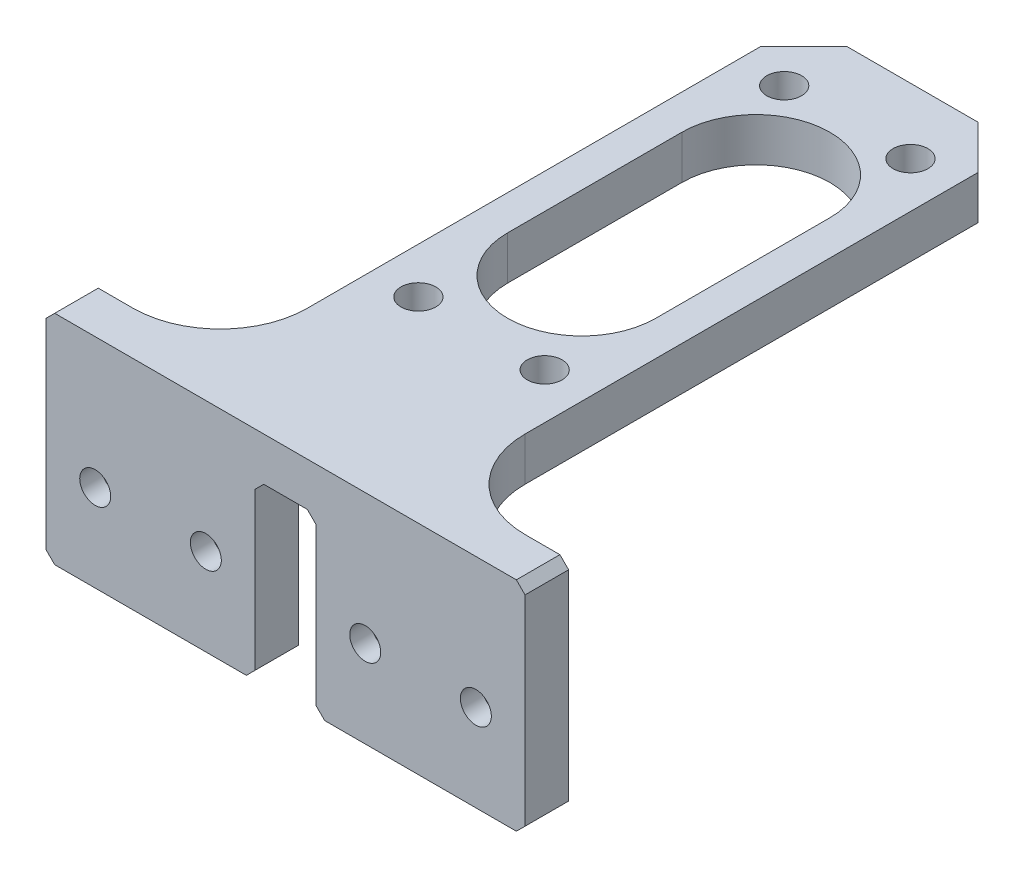
SolidWorks part; units mm, degrees
ref_plane "Front Plane" through (0, 0, 0) normal (0, 0, 1) x (1, 0, 0)
ref_plane "Top Plane" through (0, 0, 0) normal (0, 1, 0) x (1, 0, 0)
ref_plane "Right Plane" through (0, 0, 0) normal (1, 0, 0) x (0, 0, -1)
sketch "Sketch1" plane through (0, 0, 0) normal (0, 1, 0) x (1, 0, 0)
  line L0 (0, 0) -> (0, 23.7757) construction
  line L1 (-12.5, -36) -> (12.5, -36)
  line L2 (-12.5, -36) -> (-12.5, 36)
  line L3 (-12.5, 36) -> (12.5, 36)
  line L4 (12.5, -36) -> (12.5, 36)
  line L5 (-12.5, -36) -> (12.5, 36) construction
  line L6 (-12.5, 36) -> (12.5, -36) construction
  line L7 (-12.5, -36) -> (-27.5, -36)
  line L8 (-12.5, -36) -> (-12.5, -31)
  line L9 (-12.5, -31) -> (-27.5, -31)
  line L10 (-27.5, -36) -> (-27.5, -31)
  line L11 (12.5, -36) -> (27.5, -36)
  line L12 (12.5, -36) -> (12.5, -31)
  line L13 (12.5, -31) -> (27.5, -31)
  line L14 (27.5, -36) -> (27.5, -31)
  point P0 (0, 0)
  dimension "D1" = 25
  dimension "D2" = 72
  dimension "D3" = 55
  dimension "D4" = 5
extrude "Boss-Extrude1" add sketch "Sketch1" along normal blind 5 contours L1 L4 L3 L2 | L10 L7 L2 L9 | L11 L14 L13 L4
sketch "Sketch2" plane through (0, 5, 0) normal (0, 1, 0) x (1, 0, 0)
  line L0 (0, 0) -> (0, 22.8648) construction
  line L1 (-12.5, 36) -> (12.5, 36) construction
  line L2 (-27.5, -36) -> (27.5, -36) construction
  circle A0 centre (-7.25, 28.5) radius 2
  circle A1 centre (7.25, 28.5) radius 2
  circle A2 centre (-7.25, -13.5) radius 2
  circle A3 centre (7.25, -13.5) radius 2
  dimension "D3" = 4
  dimension "D1" = 14.5
  dimension "D2" = 7.5
  dimension "D4" = 22.5
extrude "Cut-Extrude1" cut sketch "Sketch2" against normal through all
chamfer "Chamfer1" distance 5 angle 45 2 edges at (-12.5, 2.5, -36) (12.5, 2.5, -36)
sketch "Sketch3" plane through (0, 5, 0) normal (0, 1, 0) x (1, 0, 0)
  line L0 (0, -2) -> (0, 18) construction
  line L1 (-8.5, -2) -> (-8.5, 18)
  line L2 (8.5, -2) -> (8.5, 18)
  line L4 (-7.5, 36) -> (7.5, 36) construction
  arc A0 (-8.5, -2) -> (8.5, -2) centre (0, -2) ccw
  arc A1 (8.5, 18) -> (-8.5, 18) centre (0, 18) ccw
  point P2 (0, 8)
  dimension "D2" = 20
  dimension "D1" = 17
  dimension "D3" = 18
extrude "Cut-Extrude2" cut sketch "Sketch3" against normal through all
sketch "Sketch5" plane through (0, 0, 0) normal (0, -1, 0) x (-1, 0, 0)
  line L0 (0, 0) -> (0, 7.4775) construction
  line L1 (27.5, -36) -> (3.5, -36)
  line L2 (27.5, -36) -> (27.5, -31)
  line L3 (27.5, -31) -> (3.5, -31)
  line L4 (3.5, -36) -> (3.5, -31)
  line L5 (-27.5, -36) -> (-3.5, -36)
  line L6 (-27.5, -36) -> (-27.5, -31)
  line L7 (-27.5, -31) -> (-3.5, -31)
  line L8 (-3.5, -36) -> (-3.5, -31)
  line L9 (-12.5, -31) -> (-27.5, -31) construction
  line L10 (12.5, -31) -> (27.5, -31) construction
  dimension "D1" = 7
extrude "Boss-Extrude3" add sketch "Sketch5" along normal blind 20
fillet "Fillet2" radius 10 2 edges at (-12.5, 2.5, 31) (12.5, 2.5, 31)
chamfer "Chamfer3" distance 1 angle 45 8 edges at (27.5, 5, 33.5) (27.5, -20, 33.5) (-27.5, 5, 33.5) (-27.5, -20, 33.5) (-3.5, -20, 33.5) (3.5, -20, 33.5) (-3.5, 0, 33.5) (3.5, 0, 33.5)
hole_wizard "Hole1" positions "Sketch8" profile "Sketch7" legacy end condition through all
sketch "Sketch8" plane through (0, 0, 31) normal (0, 0, -1) x (-1, 0, 0)
  line L0 (0, 0) -> (0, -8.6827) construction
  line L2 (-21.85, -10) -> (-9.15, -10) construction
  line L3 (-15.5, -10) -> (-15.5, -5.4682) construction
  line L5 (-27.5, 4) -> (-27.5, -19) construction
  line L6 (-4.5, -20) -> (-26.5, -20) construction
  point P0 (-21.85, -10)
  point P2 (-9.15, -10)
  point P4 (9.15, -10)
  point P6 (21.85, -10)
  dimension "D1" = 12.7
  dimension "D2" = 12
  dimension "D3" = 10
sketch "Sketch7" plane through (21.85, -10, 31) normal (1, 0, 0) x (0, 1, 0)
  line L0 (0, 0) -> (0, 5)
  line L1 (0, 5) -> (1.778, 5)
  line L2 (1.778, 5) -> (1.778, 2.54)
  line L3 (1.778, 2.54) -> (3.429, 2.54)
  line L4 (3.429, 2.54) -> (3.429, 0)
  line L5 (3.429, 0) -> (0, 0)
  line L6 (0, 110) -> (0, -10) construction
  dimension "Diameter" = 3.556
  dimension "Depth" = 5
  dimension "C-Bore Diameter" = 6.858
  dimension "C-Bore Depth" = 2.54
chamfer "Chamfer4" distance 0.5 angle 45 4 edges at (-25.279, -10, 31) (-12.579, -10, 31) (5.721, -10, 31) (18.421, -10, 31)
